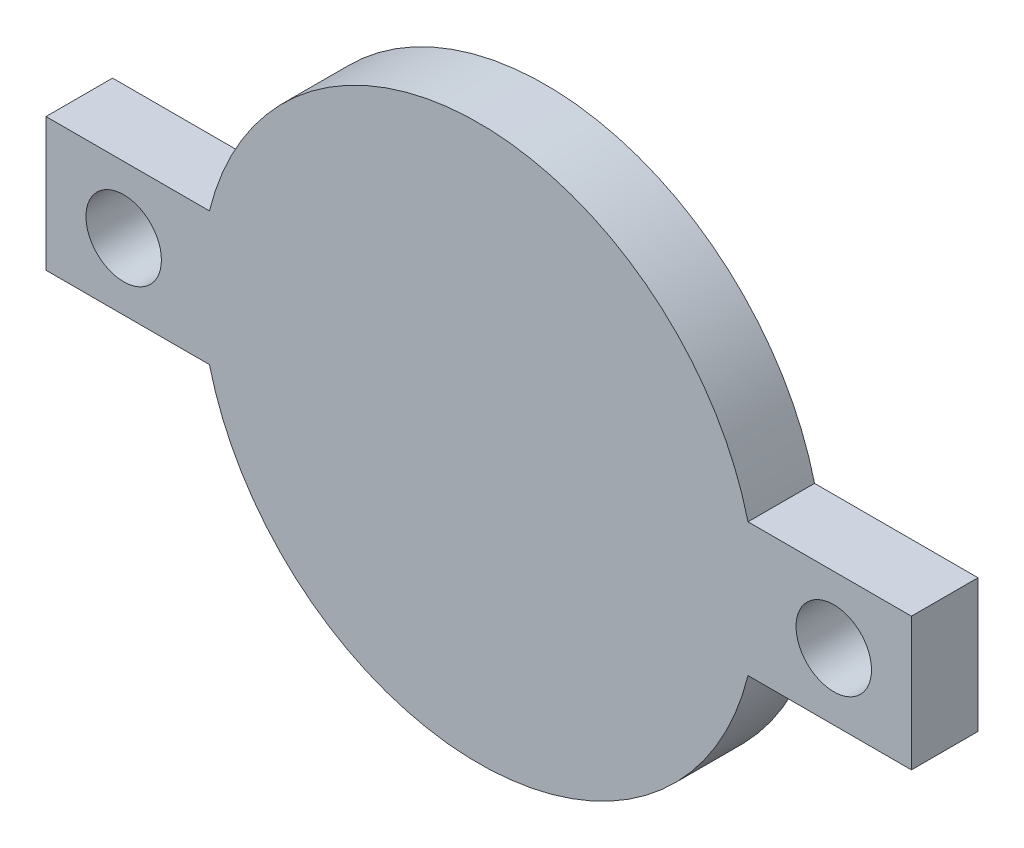
SolidWorks part; units mm, degrees
ref_plane "Front Plane" through (0, 0, 0) normal (0, 0, 1) x (1, 0, 0)
ref_plane "Top Plane" through (0, 0, 0) normal (0, 1, 0) x (1, 0, 0)
ref_plane "Right Plane" through (0, 0, 0) normal (1, 0, 0) x (0, 0, -1)
sketch "Sketch2" plane through (0, 0, 0) normal (0, 0, 1) x (1, 0, 0)
  line L5 (-23.85, -8.1374) -> (-23.85, -10.8824)
  line L6 (-17.8653, -3) -> (-10.5, -3)
  line L7 (-10.5, -3) -> (-10.5, 3)
  line L8 (-10.5, 3) -> (-17.8653, 3)
  line L9 (-23.85, 10.8824) -> (-23.85, 8.1374)
  line L10 (-23.85, -8.1374) -> (-23.85, -10.8824)
  line L11 (-17.8653, -3) -> (-10.5, -3)
  line L12 (-10.5, -3) -> (-10.5, 3)
  line L13 (-10.5, 3) -> (-17.8653, 3)
  line L14 (-23.85, 10.8824) -> (-23.85, 8.1374)
  line L15 (-36.15, 8.1374) -> (-36.15, 10.8824)
  line L16 (-42.1347, 3) -> (-49.5, 3)
  line L17 (-49.5, 3) -> (-49.5, -3)
  line L18 (-49.5, -3) -> (-42.1347, -3)
  line L19 (-36.15, -10.8824) -> (-36.15, -8.1374)
  line L20 (-36.15, 8.1374) -> (-36.15, 10.8824)
  line L21 (-42.1347, 3) -> (-49.5, 3)
  line L22 (-49.5, 3) -> (-49.5, -3)
  line L23 (-49.5, -3) -> (-42.1347, -3)
  line L24 (-36.15, -10.8824) -> (-36.15, -8.1374)
  circle A0 centre (-30, 0) radius 10.2
  circle A1 centre (-30, 0) radius 12.5
  circle A2 centre (-14, 0) radius 1.7 construction
  arc A3 (-23.85, -8.1374) -> (-23.85, 8.1374) centre (-30, 0) ccw
  arc A4 (-23.85, -10.8824) -> (-17.8653, -3) centre (-30, 0) ccw
  arc A5 (-17.8653, 3) -> (-23.85, 10.8824) centre (-30, 0) ccw
  arc A6 (-23.85, -8.1374) -> (-23.85, 8.1374) centre (-30, 0) ccw
  arc A7 (-23.85, -10.8824) -> (-17.8653, -3) centre (-30, 0) ccw
  arc A8 (-17.8653, 3) -> (-23.85, 10.8824) centre (-30, 0) ccw
  arc A9 (-36.15, 8.1374) -> (-36.15, -8.1374) centre (-30, 0) ccw
  arc A10 (-36.15, 10.8824) -> (-42.1347, 3) centre (-30, 0) ccw
  arc A11 (-42.1347, -3) -> (-36.15, -10.8824) centre (-30, 0) ccw
  arc A12 (-36.15, 8.1374) -> (-36.15, -8.1374) centre (-30, 0) ccw
  arc A13 (-36.15, 10.8824) -> (-42.1347, 3) centre (-30, 0) ccw
  arc A14 (-42.1347, -3) -> (-36.15, -10.8824) centre (-30, 0) ccw
  circle A15 centre (-14, 0) radius 1.7
  circle A16 centre (-46, 0) radius 1.7 construction
  circle A17 centre (-46, 0) radius 1.7
  circle M19 centre (-46, 0) radius 1.7
  arc M20 (-36.15, -8.1374) -> (-36.15, 8.1374) centre (-30, 0) cw
  line M21 (-36.15, 8.1374) -> (-36.15, 10.8824)
  arc M22 (-36.15, 10.8824) -> (-42.1347, 3) centre (-30, 0) ccw
  line M23 (-42.1347, 3) -> (-49.5, 3)
  line M24 (-49.5, 3) -> (-49.5, -3)
  line M25 (-49.5, -3) -> (-42.1347, -3)
  arc M26 (-42.1347, -3) -> (-36.15, -10.8824) centre (-30, 0) ccw
  line M27 (-36.15, -10.8824) -> (-36.15, -8.1374)
  dimension "D1" = 0
  dimension "D2" = 0
extrude "Boss-Extrude1" add sketch "Sketch2" along normal blind 3 contours A1 L11 L12 L13 A15 | A1 L14 A0 L10 | A1 L10 A0 M27 | A1 M22 M26 M27 M20 M21 | A0 M20 | L14 A1 A0 M21 | A1 M23 M24 M25 M19
sketch "Sketch3" plane through (0, 0, 0) normal (0, 0, -1) x (-1, 0, 0)
  circle A0 centre (30, 0) radius 10.2
  dimension "D1" = 20.4
extrude "Cut-Extrude1" cut sketch "Sketch3" against normal blind 1
